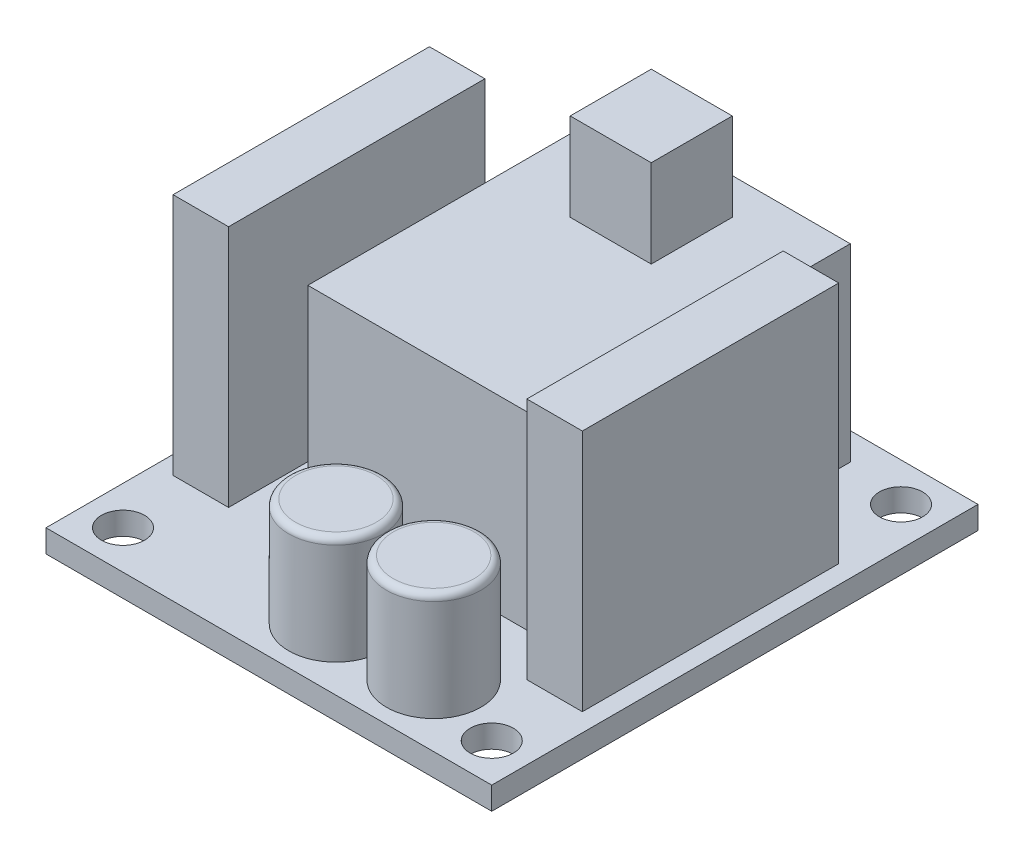
SolidWorks part; units mm, degrees
ref_plane "Front Plane" through (0, 0, 0) normal (0, 0, 1) x (1, 0, 0)
ref_plane "Top Plane" through (0, 0, 0) normal (0, 1, 0) x (1, 0, 0)
ref_plane "Right Plane" through (0, 0, 0) normal (1, 0, 0) x (0, 0, -1)
sketch "Sketch1" plane through (0, 0, 0) normal (0, 1, 0) x (1, 0, 0)
  line L1 (-16.5, -18) -> (16.5, -18)
  line L2 (-16.5, -18) -> (-16.5, 18)
  line L3 (-16.5, 18) -> (16.5, 18)
  line L4 (16.5, -18) -> (16.5, 18)
  line L5 (-16.5, -18) -> (16.5, 18) construction
  line L6 (-16.5, 18) -> (16.5, -18) construction
  line L7 (13.65, -15.15) -> (-13.65, -15.15) construction
  line L8 (13.65, -15.15) -> (13.65, 15.15) construction
  line L9 (13.65, 15.15) -> (-13.65, 15.15) construction
  line L10 (-13.65, -15.15) -> (-13.65, 15.15) construction
  line L11 (13.65, -15.15) -> (-13.65, 15.15) construction
  line L12 (13.65, 15.15) -> (-13.65, -15.15) construction
  circle A0 centre (-13.65, 15.15) radius 1.6
  circle A1 centre (13.65, 15.15) radius 1.6
  circle A2 centre (13.65, -15.15) radius 1.6
  circle A3 centre (-13.65, -15.15) radius 1.6
  point P0 (0, 0)
  point P10 (0, 0)
  dimension "D5" = 3.2
  dimension "D1" = 33
  dimension "D2" = 36
  dimension "D3" = 27.3
  dimension "D4" = 30.3
extrude "Boss-Extrude1" add sketch "Sketch1" along normal blind 1.68
sketch "Sketch2" plane through (0, 1.68, 0) normal (0, 1, 0) x (1, 0, 0)
  line L1 (-8.3519, 15.9824) -> (9.0612, 15.9824)
  line L2 (-8.3519, 15.9824) -> (-8.3519, -6.7622)
  line L3 (-8.3519, -6.7622) -> (9.0612, -6.7622)
  line L4 (9.0612, 15.9824) -> (9.0612, -6.7622)
extrude "Boss-Extrude2" add sketch "Sketch2" along normal blind 14
sketch "Sketch3" plane through (0, 15.68, 0) normal (0, 1, 0) x (1, 0, 0)
  line L0 (0, -12.199) -> (0, 12.199) construction
  line L1 (-3, 7.3085) -> (3, 7.3085)
  line L2 (-3, 7.3085) -> (-3, 13.3085)
  line L3 (-3, 13.3085) -> (3, 13.3085)
  line L4 (3, 7.3085) -> (3, 13.3085)
  line L5 (-3, 7.3085) -> (3, 13.3085) construction
  line L6 (-3, 13.3085) -> (3, 7.3085) construction
  point P0 (0, 10.3085)
  dimension "D1" = 6
extrude "Boss-Extrude3" add sketch "Sketch3" along normal blind 6.5
sketch "Sketch4" plane through (0, 1.68, 0) normal (0, 1, 0) x (1, 0, 0)
  line L1 (-15.1509, 9.0367) -> (-11.0421, 9.0367)
  line L2 (-15.1509, 9.0367) -> (-15.1509, -9.9416)
  line L3 (-15.1509, -9.9416) -> (-11.0421, -9.9416)
  line L4 (-11.0421, 9.0367) -> (-11.0421, -9.9416)
extrude "Boss-Extrude4" add sketch "Sketch4" along normal blind 18
mirror "Mirror1" about plane through (0, 0, 0) normal (1, 0, 0) of "Boss-Extrude4"
sketch "Sketch5" plane through (0, 1.68, 0) normal (0, 1, 0) x (1, 0, 0)
  circle A0 centre (7.6168, -13.4143) radius 3.4954
  circle A1 centre (0.3803, -13.4143) radius 3.4954
extrude "Boss-Extrude5" add sketch "Sketch5" along normal blind 8
fillet "Fillet1" radius 0.5 2 edges at (0.3803, 9.68, 16.9097) (7.6168, 9.68, 16.9097)
